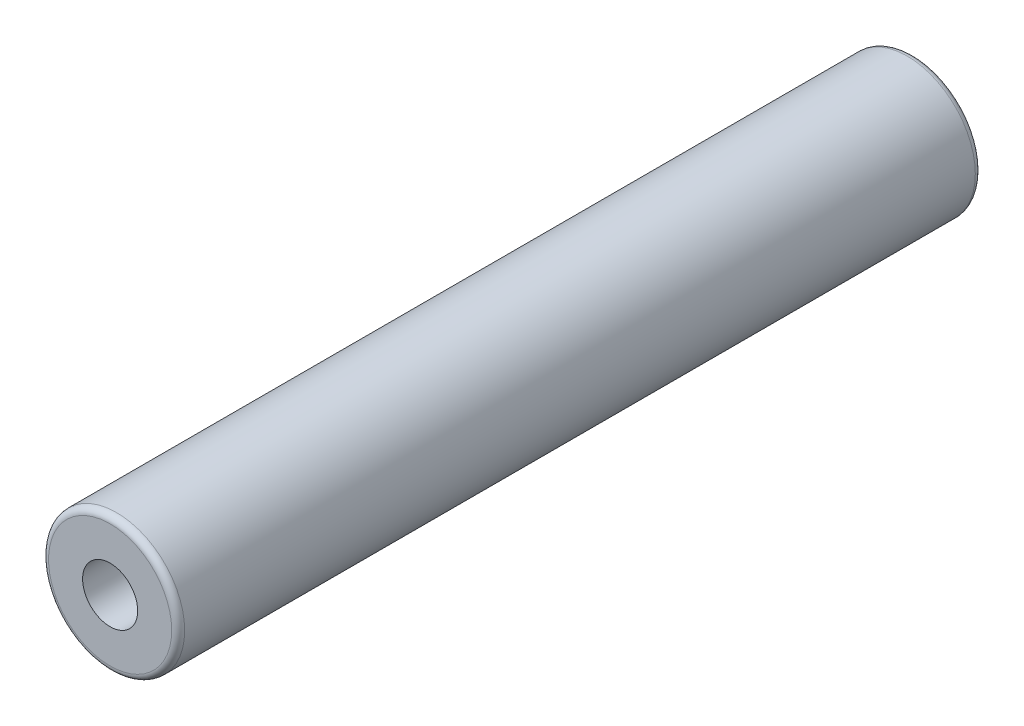
SolidWorks part; units mm, degrees
material "AISI 4340 Aço recozido"
ref_plane "Plano frontal" through (0, 0, 0) normal (0, 0, 1) x (1, 0, 0)
ref_plane "Plano superior" through (0, 0, 0) normal (0, 1, 0) x (1, 0, 0)
ref_plane "Plano direito" through (0, 0, 0) normal (1, 0, 0) x (0, 0, -1)
sketch "Esboço1" plane through (0, 0, 0) normal (0, 0, 1) x (1, 0, 0)
  circle A0 centre (-70, 54) radius 10.5
  dimension "D1" = 21
extrude "Ressalto-extrusão1" add sketch "Esboço1" against normal blind 124
fillet "Filete1" radius 1 2 edges at (-59.5, 54, -124) (-59.5, 54, 0)
hole_wizard "Broca de rosquear para tarraxa de M101" positions "Esboço2" profile "Esboço3" hole size "M10" standard "ISO"
sketch "Esboço2" plane through (0, 0, 0) normal (0, 0, 1) x (1, 0, 0)
  circle A0 centre (-70, 54) radius 9.5 construction
  point P0 (-70, 54)
sketch "Esboço3" plane through (-70, 54, 0) normal (1, 0, 0) x (0, -1, 0)
  line L0 (0, 0) -> (0, 27.5537)
  line L1 (0, 27.5537) -> (4.25, 25)
  line L2 (4.25, 25) -> (4.25, 0)
  line L5 (4.25, 0) -> (0, 0)
  line L10 (0, 27.5537) -> (-4.25, 25) construction
  line L11 (0, -6.35) -> (0, 107.95) construction
  dimension "Hole Dia." = 8.5
  dimension "Hole Depth" = 25
  dimension "Drill Angle" = 118
hole_wizard "Broca de rosquear para tarraxa de M102" positions "Esboço4" profile "Esboço5" hole size "M10" standard "ISO"
sketch "Esboço4" plane through (0, 0, -124) normal (0, 0, -1) x (-1, 0, 0)
  circle A0 centre (70, 54) radius 9.5 construction
  point P0 (70, 54)
sketch "Esboço5" plane through (-70, 54, -124) normal (1, 0, 0) x (0, 1, 0)
  line L0 (0, 0) -> (0, 27.5537)
  line L1 (0, 27.5537) -> (4.25, 25)
  line L2 (4.25, 25) -> (4.25, 0)
  line L5 (4.25, 0) -> (0, 0)
  line L10 (0, 27.5537) -> (-4.25, 25) construction
  line L11 (0, -6.35) -> (0, 107.95) construction
  dimension "Hole Dia." = 8.5
  dimension "Hole Depth" = 25
  dimension "Drill Angle" = 118
